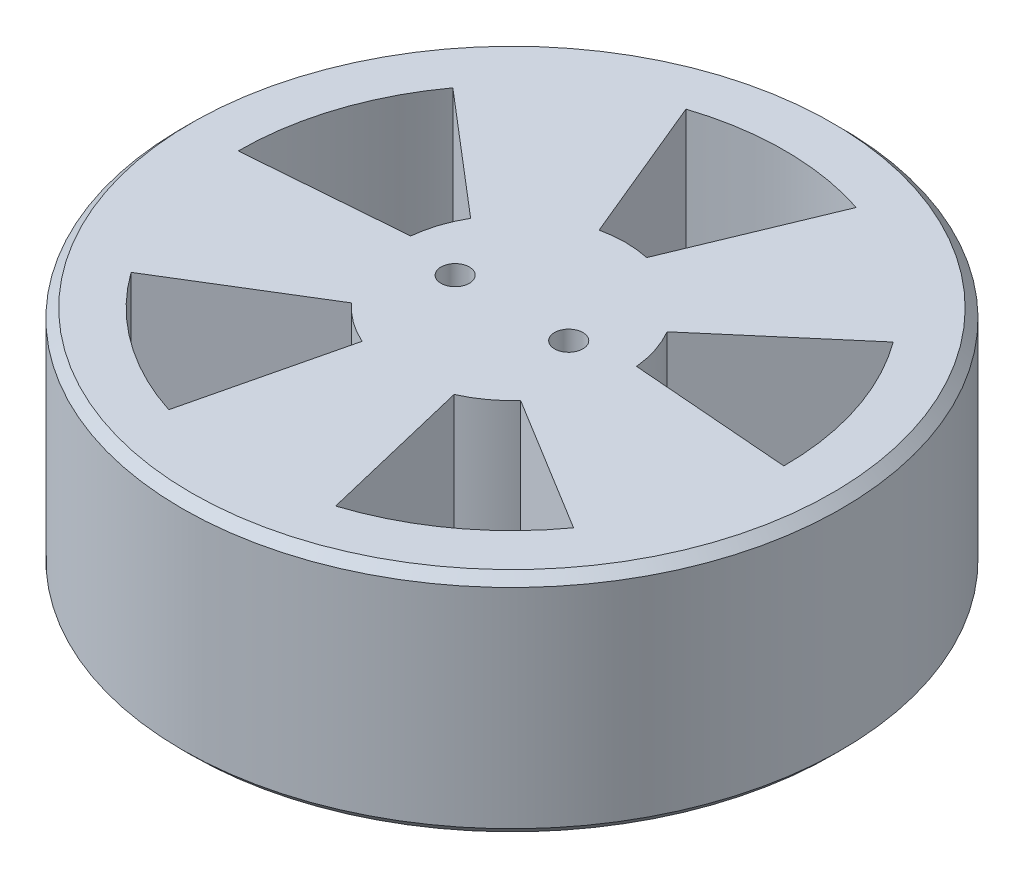
SolidWorks part; units mm, degrees
ref_plane "Front Plane" through (0, 0, 0) normal (0, 0, 1) x (1, 0, 0)
ref_plane "Top Plane" through (0, 0, 0) normal (0, 1, 0) x (1, 0, 0)
ref_plane "Right Plane" through (0, 0, 0) normal (1, 0, 0) x (0, 0, -1)
sketch "Sketch2" plane through (0, 0, 0) normal (0, 1, 0) x (1, 0, 0)
  circle A0 centre (0, 0) radius 73.7235
  dimension "D1" = 147.447
extrude "Boss-Extrude1" add sketch "Sketch2" along normal blind 50.8
chamfer "Chamfer1" distance 2.032 angle 45 2 edges at (0, 0, 73.7235) (0, 50.8, 73.7235)
sketch "Sketch3" plane through (0, 50.8, 0) normal (0, 1, 0) x (1, 0, 0)
  line L0 (-12.7, 0) -> (0, 0) construction
  line L1 (0, 0) -> (12.7, 0) construction
  circle A0 centre (0, 0) radius 25.4 construction
  circle A1 centre (-12.7, 0) radius 3.175
  circle A2 centre (12.7, 0) radius 3.175
  dimension "D1" = 6.35
  dimension "D4" = 50.8
  dimension "D2" = 12.7
  dimension "D3" = 12.7
extrude "Cut-Extrude1" cut sketch "Sketch3" against normal through all both and the other way through all
sketch "Sketch4" plane through (0, 50.8, 0) normal (0, 1, 0) x (1, 0, 0)
  line L0 (0, 25.4) -> (0, 61.0235) construction
  line L1 (-5.3238, 24.8358) -> (-19.05, 57.9738)
  line L2 (5.3238, 24.8358) -> (19.05, 57.9738)
  line L3 (21.9751, 12.7379) -> (49.2496, 36.0325)
  line L4 (25.2654, 2.6115) -> (61.0232, -0.2027)
  line L5 (18.9052, -16.9634) -> (49.4879, -35.7045)
  line L6 (10.2911, -23.2218) -> (18.6644, -58.0991)
  line L7 (-10.2911, -23.2218) -> (-18.6644, -58.0991)
  line L8 (-18.9052, -16.9634) -> (-49.4879, -35.7045)
  line L9 (-25.2654, 2.6115) -> (-61.0232, -0.2027)
  line L10 (-21.9751, 12.7379) -> (-49.2496, 36.0325)
  arc A0 (5.3238, 24.8358) -> (-5.3238, 24.8358) centre (0, 0) ccw
  arc A7 (-19.05, 57.9738) -> (19.05, 57.9738) centre (0, 0) cw
  circle A9 centre (0, 0) radius 73.7235 construction
  arc A20 (25.2654, 2.6115) -> (21.9751, 12.7379) centre (0, 0) ccw
  arc A21 (61.0232, -0.2027) -> (49.2496, 36.0325) centre (0, 0) ccw
  arc A22 (10.2911, -23.2218) -> (18.9052, -16.9634) centre (0, 0) ccw
  arc A23 (18.6644, -58.0991) -> (49.4879, -35.7045) centre (0, 0) ccw
  arc A24 (-18.9052, -16.9634) -> (-10.2911, -23.2218) centre (0, 0) ccw
  arc A25 (-49.4879, -35.7045) -> (-18.6644, -58.0991) centre (0, 0) ccw
  arc A26 (-21.9751, 12.7379) -> (-25.2654, 2.6115) centre (0, 0) ccw
  arc A27 (-49.2496, 36.0325) -> (-61.0232, -0.2027) centre (0, 0) ccw
  point P5 (0, 0)
  point P12 (0, 50.3165)
  point P30 (0, 0)
  point P32 (0, 0)
  dimension "D1" = 50.8
  dimension "D2" = 12.7
  dimension "D3" = 22.5
  dimension "D4" = 45
  dimension "D5" = 19.05
  dimension "D6" = 19.05
  dimension "D7" = 5
extrude "Cut-Extrude2" cut sketch "Sketch4" against normal through all both and the other way through all contours L9 A27 L10 A26 | L7 A25 L8 A24 | L5 A23 L6 A22 | L3 A21 L4 A20 | A7 L2 A0 L1
equation "\"OD\"= 5.820"
equation "\"offset\" = 0.015"
equation "\"L\" = 2"
equation "\"ID\"= 3"
equation "\"D1@Sketch2\"=\"OD\"-\"offset\""
equation "\"D1@Boss-Extrude1\"=\"L\""
